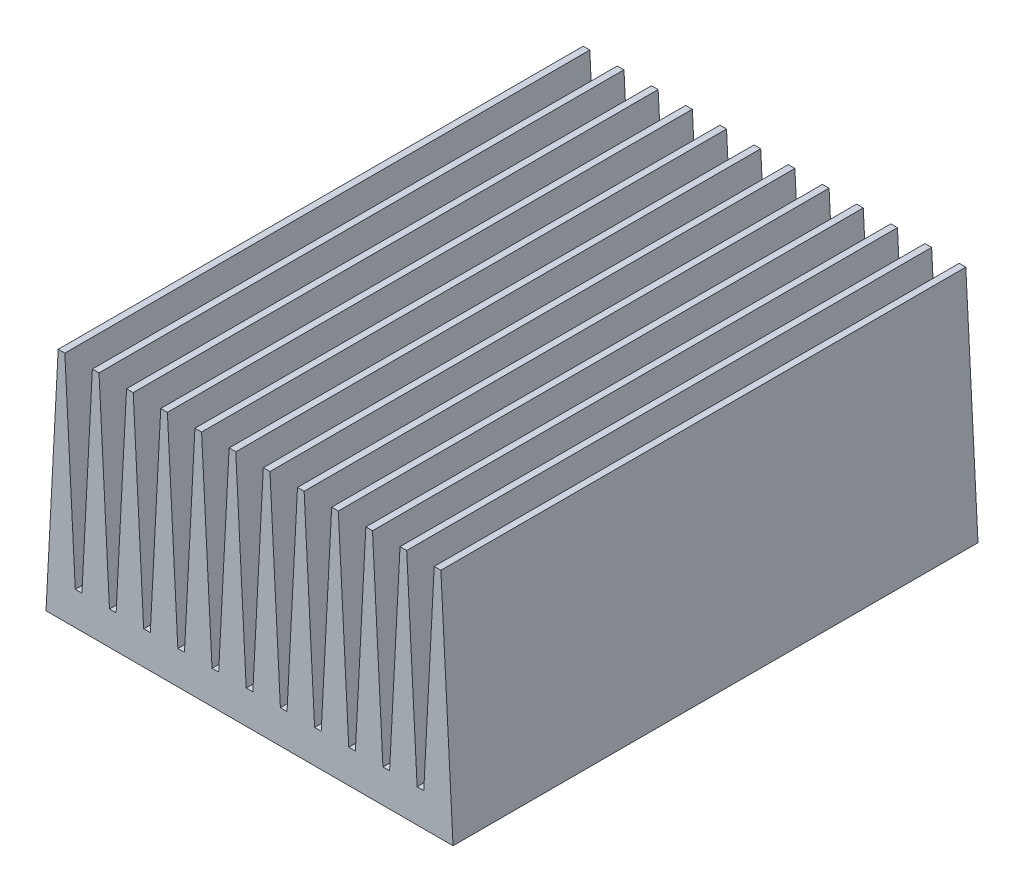
SolidWorks part; units mm, degrees
material "1060 Alloy"
ref_plane "Front Plane" through (0, 0, 0) normal (0, 0, 1) x (1, 0, 0)
ref_plane "Top Plane" through (0, 0, 0) normal (0, 1, 0) x (1, 0, 0)
ref_plane "Right Plane" through (0, 0, 0) normal (1, 0, 0) x (0, 0, -1)
sketch "Sketch1" plane through (0, 0, 0) normal (0, 0, 1) x (1, 0, 0)
  line L0 (0, 0) -> (1.8343, 35)
  line L1 (1.8343, 35) -> (2.8343, 35)
  line L2 (2.8343, 35) -> (4.4065, 5)
  line L3 (4.4065, 5) -> (5.4065, 5)
  line L4 (5.4065, 5) -> (6.9787, 35)
  line L5 (6.9787, 35) -> (7.9787, 35)
  line L6 (7.9787, 35) -> (9.551, 5)
  line L7 (9.551, 5) -> (10.551, 5)
  line L8 (10.551, 5) -> (12.1232, 35)
  line L9 (12.1232, 35) -> (13.1232, 35)
  line L10 (13.1232, 35) -> (14.6954, 5)
  line L11 (14.6954, 5) -> (15.6954, 5)
  line L12 (15.6954, 5) -> (17.2677, 35)
  line L13 (17.2677, 35) -> (18.2677, 35)
  line L14 (18.2677, 35) -> (19.8399, 5)
  line L15 (19.8399, 5) -> (20.8399, 5)
  line L16 (20.8399, 5) -> (22.4121, 35)
  line L17 (22.4121, 35) -> (23.4121, 35)
  line L18 (23.4121, 35) -> (24.9844, 5)
  line L19 (24.9844, 5) -> (25.9844, 5)
  line L20 (25.9844, 5) -> (27.5566, 35)
  line L21 (27.5566, 35) -> (28.5566, 35)
  line L22 (28.5566, 35) -> (30.1288, 5)
  line L23 (30.1288, 5) -> (31.1288, 5)
  line L24 (31.1288, 5) -> (32.7011, 35)
  line L25 (32.7011, 35) -> (33.7011, 35)
  line L26 (33.7011, 35) -> (35.2733, 5)
  line L27 (35.2733, 5) -> (36.2733, 5)
  line L28 (36.2733, 5) -> (37.8455, 35)
  line L29 (37.8455, 35) -> (38.8455, 35)
  line L30 (38.8455, 35) -> (40.4178, 5)
  line L31 (40.4178, 5) -> (41.4178, 5)
  line L32 (41.4178, 5) -> (42.99, 35)
  line L33 (42.99, 35) -> (43.99, 35)
  line L34 (43.99, 35) -> (45.5622, 5)
  line L35 (45.5622, 5) -> (46.5622, 5)
  line L36 (46.5622, 5) -> (48.1345, 35)
  line L37 (48.1345, 35) -> (49.1345, 35)
  line L38 (49.1345, 35) -> (50.7067, 5)
  line L39 (50.7067, 5) -> (51.7067, 5)
  line L40 (51.7067, 5) -> (53.2789, 35)
  line L41 (53.2789, 35) -> (54.2789, 35)
  line L42 (54.2789, 35) -> (55.8512, 5)
  line L43 (55.8512, 5) -> (56.8512, 5)
  line L44 (56.8512, 5) -> (58.4234, 35)
  line L45 (58.4234, 35) -> (59.4234, 35)
  line L46 (59.4234, 35) -> (61.2577, 0)
  line L47 (0, 0) -> (61.2577, 0)
  dimension "D1" = 87
  dimension "D2" = 87
  dimension "D3" = 87
  dimension "D4" = 87
  dimension "D5" = 1
  dimension "D6" = 1
  dimension "D7" = 1
  dimension "D8" = 35
  dimension "D9" = 5
extrude "Boss-Extrude1" add sketch "Sketch1" along normal mid plane 79
equation "\"A\"= 35"
equation "\"B\"= 79"
equation "\"C\"= 1"
equation "\"D5@Sketch1\"=\"C\""
equation "\"D6@Sketch1\"=\"C\""
equation "\"D7@Sketch1\"=\"C\""
equation "\"D8@Sketch1\"=\"A\""
equation "\"D1@Boss-Extrude1\"=\"B\""
